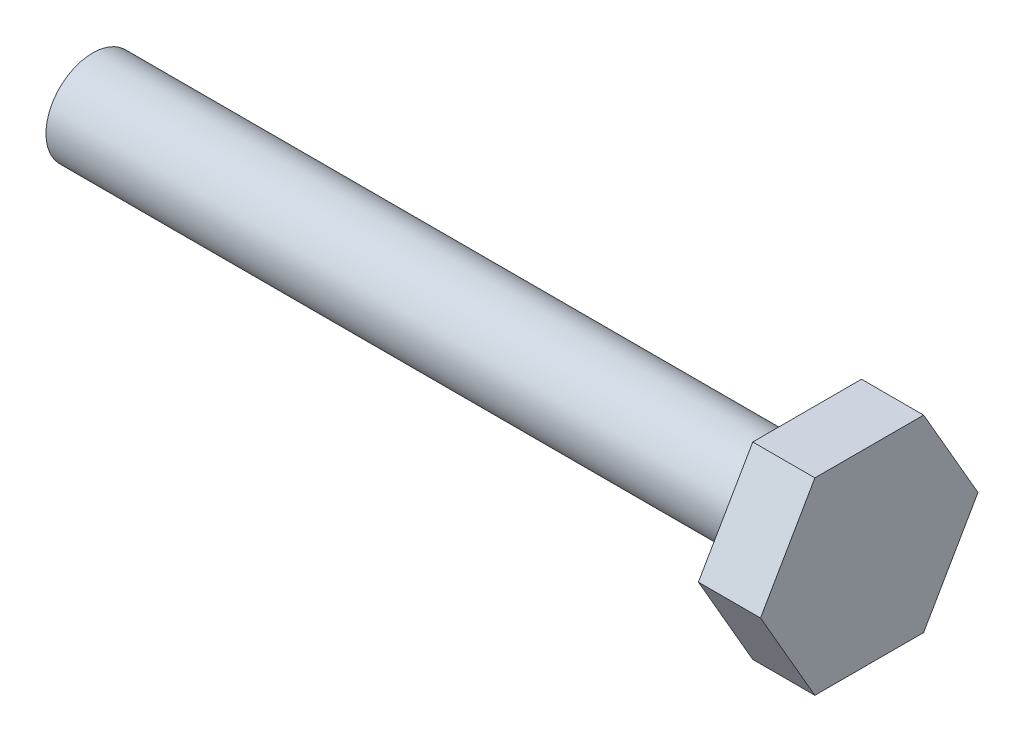
SolidWorks part; units mm, degrees
ref_plane "Płaszczyzna przednia" through (0, 0, 0) normal (0, 0, 1) x (1, 0, 0)
ref_plane "Płaszczyzna górna" through (0, 0, 0) normal (0, 1, 0) x (1, 0, 0)
ref_plane "Płaszczyzna prawa" through (0, 0, 0) normal (1, 0, 0) x (0, 0, -1)
sketch "Szkic1" plane through (0, 0, 0) normal (0, 0, 1) x (1, 0, 0)
  line L0 (0, 0) -> (-50, 0)
  line L1 (-50, 0) -> (-50, 3)
  line L2 (-50, 3) -> (-4, 3)
  line L3 (-4, 3) -> (-4, 7)
  line L4 (-4, 7) -> (0, 7)
  line L5 (0, 7) -> (0, 0)
  dimension "D1" = 50
  dimension "D2" = 4
  dimension "D3" = 46
  dimension "D4" = 7
  dimension "D5" = 3
revolve "Obrót1" add sketch "Szkic1" angle 360 about L0
sketch "Szkic3" plane through (0, 0, 0) normal (1, 0, 0) x (0, 0, -1)
  line L1 (7, 0) -> (3.5, 6.0622)
  line L2 (3.5, 6.0622) -> (-3.5, 6.0622)
  line L3 (-3.5, 6.0622) -> (-7, 0)
  line L4 (-7, 0) -> (-3.5, -6.0622)
  line L5 (-3.5, -6.0622) -> (3.5, -6.0622)
  line L6 (3.5, -6.0622) -> (7, 0)
  circle A0 centre (0, 0) radius 6.0622 construction
  circle A1 centre (0, 0) radius 7 construction
  circle A2 centre (0, 0) radius 7
  circle M7 centre (0, 0) radius 7
extrude "Wytnij-wyciągnięcie2" cut sketch "Szkic3" against normal up to surface (4 mm away) contours L3 M7 | L2 M7 | L1 M7 | L6 M7 | L5 M7 | L4 M7 up to face at (-4, 7, 0)
